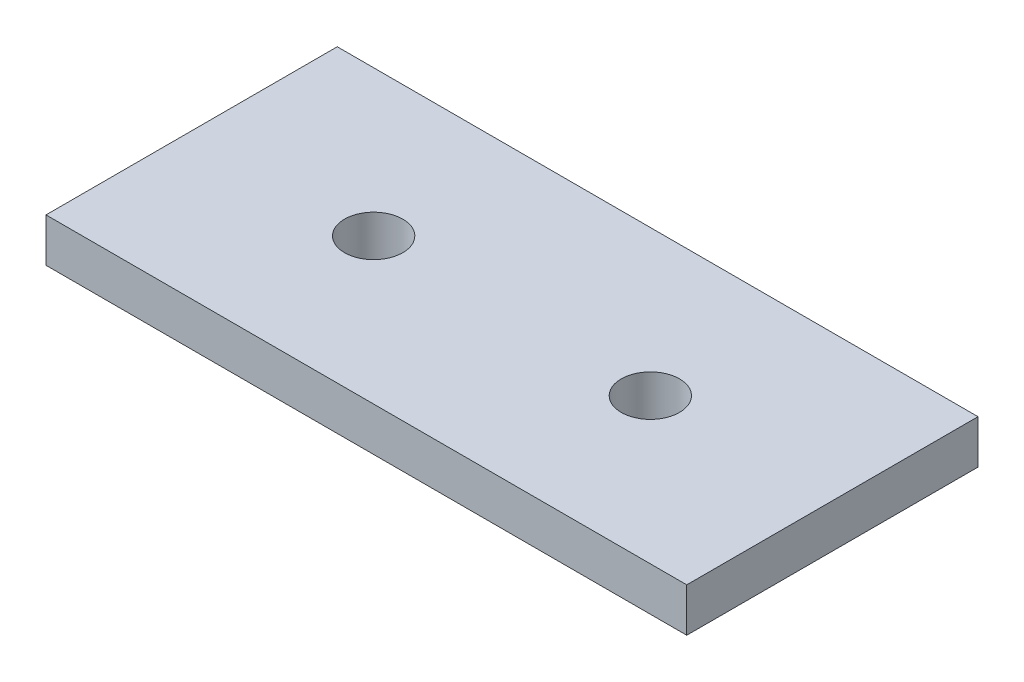
SolidWorks part; units mm, degrees
material "Acrylic (Medium-high impact)"
ref_plane "Front Plane" through (0, 0, 0) normal (0, 0, 1) x (1, 0, 0)
ref_plane "Top Plane" through (0, 0, 0) normal (0, 1, 0) x (1, 0, 0)
ref_plane "Right Plane" through (0, 0, 0) normal (1, 0, 0) x (0, 0, -1)
sketch "Sketch1" plane through (0, 0, 0) normal (0, 1, 0) x (1, 0, 0)
  line L1 (-137.9412, 9.5588) -> (-49.9412, 9.5588)
  line L2 (-137.9412, 9.5588) -> (-137.9412, -30.4412)
  line L3 (-137.9412, -30.4412) -> (-49.9412, -30.4412)
  line L4 (-49.9412, 9.5588) -> (-49.9412, -30.4412)
  dimension "D1" = 40
  dimension "D2" = 88
extrude "Boss-Extrude1" add sketch "Sketch1" along normal blind 6
sketch "Sketch3" plane through (0, 0, 0) normal (0, -1, 0) x (1, 0, 0)
  circle A2 centre (-74.9412, 10.4412) radius 4
  circle A3 centre (-112.9412, 10.4412) radius 4
extrude "Cut-Extrude1" cut sketch "Sketch3" against normal blind 6
